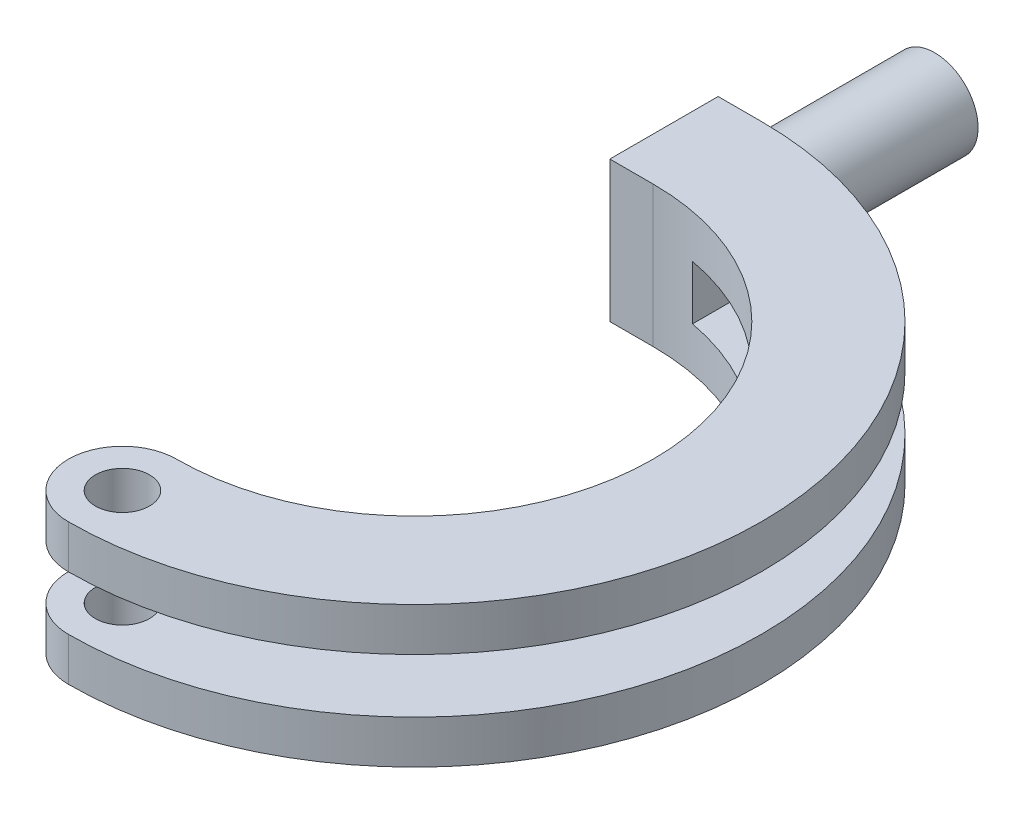
SolidWorks part; units mm, degrees
ref_plane "Front Plane" through (0, 0, 0) normal (0, 0, 1) x (1, 0, 0)
ref_plane "Top Plane" through (0, 0, 0) normal (0, 1, 0) x (1, 0, 0)
ref_plane "Right Plane" through (0, 0, 0) normal (1, 0, 0) x (0, 0, -1)
sketch "Sketch1" plane through (0, 0, 0) normal (0, 1, 0) x (1, 0, 0)
  line L2 (0, -11) -> (0, -16) construction
  line L3 (0, 11) -> (-2, 11)
  line L4 (-2, 11) -> (-2, 16)
  line L5 (-2, 16) -> (0, 16)
  arc A0 (0, -16) -> (0, 16) centre (0, 0) ccw
  arc A1 (0, -11) -> (0, 11) centre (0, 0) ccw
  arc A2 (0, -11) -> (0, -16) centre (0, -13.5) ccw
  circle A3 centre (0, -13.5) radius 1.25
  point P8 (-4.1566, 7.1833)
  point P11 (0, 0)
  dimension "D1" = 5
  dimension "D2" = 32
  dimension "D3" = 2.5
  dimension "D4" = 2
extrude "Boss-Extrude1" add sketch "Sketch1" along normal blind 2
pattern_linear "LPattern1" count 2 spacing 4.5 along (0, 1, 0) of "Boss-Extrude1"
sketch "Sketch3" plane through (0, 2, 0) normal (0, 1, 0) x (1, 0, 0)
  line L0 (-2, 16) -> (-2, 11)
  line L1 (-2, 11) -> (0, 11)
  line L3 (0, 16) -> (-2, 16)
  line L4 (2, 10.8167) -> (2, 15.8745)
  arc A0 (2, 10.8167) -> (0, 11) centre (0, 0) ccw
  arc A1 (2, 15.8745) -> (0, 16) centre (0, 0) ccw
  dimension "D1" = 4
extrude "Boss-Extrude2" add sketch "Sketch3" along normal up to surface (2.5 mm away) up to face at (3.4167, 4.5, -4.5)
sketch "Sketch4" plane through (0, 0, -16) normal (0, 0, -1) x (-1, 0, 0)
  line L0 (0, 6.5) -> (0, 0) construction
  line L1 (2, 6.5) -> (2, 0) construction
  circle A0 centre (0, 3.25) radius 2
extrude "Boss-Extrude3" add sketch "Sketch4" along normal blind 8
